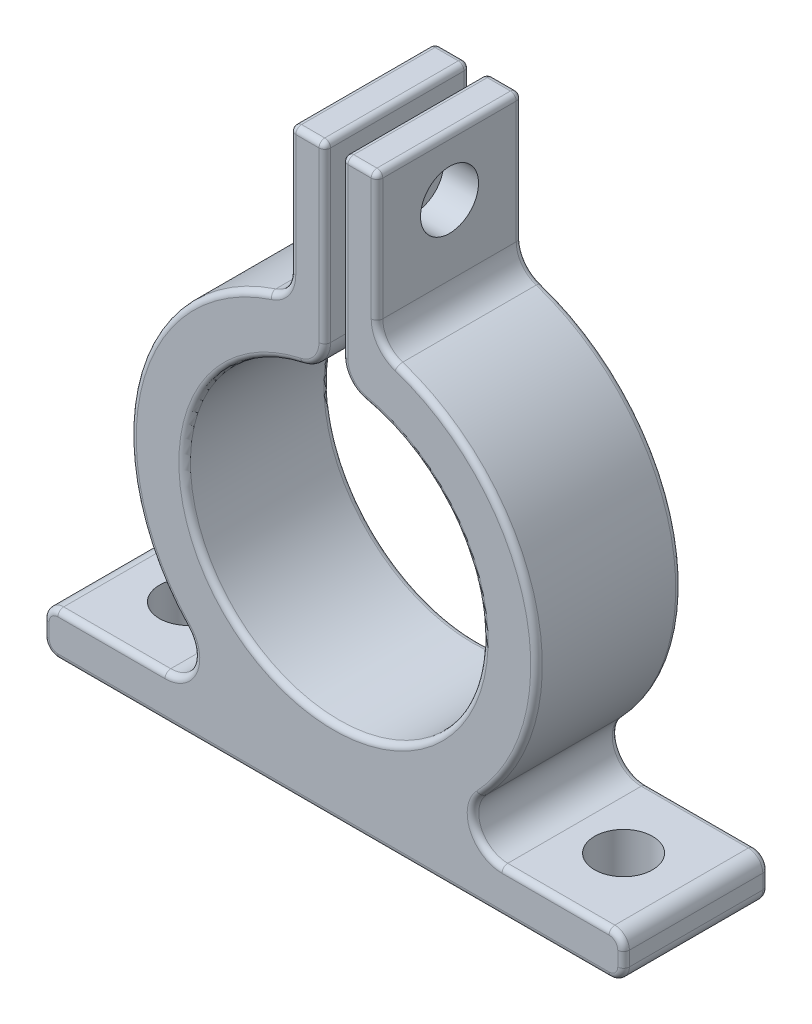
SolidWorks part; units mm, degrees
ref_plane "前视基准面" through (0, 0, 0) normal (0, 0, 1) x (1, 0, 0)
ref_plane "上视基准面" through (0, 0, 0) normal (0, 1, 0) x (1, 0, 0)
ref_plane "右视基准面" through (0, 0, 0) normal (1, 0, 0) x (0, 0, -1)
sketch "草图1" plane through (0, 0, 0) normal (0, 0, 1) x (1, 0, 0)
  line L0 (-9.5, -6.5) -> (-5.8095, -6.5)
  line L1 (0, -2.1091) -> (0, -11.8916) construction
  line L2 (-10, -7) -> (-10, -7.5)
  line L3 (-9.5, -8) -> (9.5, -8)
  line L4 (9.5, -6.5) -> (5.8095, -6.5)
  line L5 (-1.5, 11.8) -> (-1.5, 7.5993)
  line L6 (1.5, 11.8) -> (1.5, 7.5993)
  line L7 (-0.3, 11.8) -> (-0.3, 5.9914)
  line L8 (0, 0) -> (0, -2.1091) construction
  line L9 (0.3, 5.9914) -> (0.3, 11.8)
  line L10 (-1.3, 12) -> (-0.5, 12)
  line L11 (1.3, 12) -> (0.5, 12)
  line L12 (10, -7) -> (10, -7.5)
  arc A0 (-1.088, 5.0141) -> (1.088, 5.0141) centre (0, 0) ccw
  arc A1 (2.1875, 6.6494) -> (5.0833, -4.8125) centre (0, 0) cw
  arc A2 (5.0833, -4.8125) -> (5.8095, -6.5) centre (5.8095, -5.5) ccw
  arc A3 (-5.0833, -4.8125) -> (-5.8095, -6.5) centre (-5.8095, -5.5) cw
  arc A4 (10, -7) -> (9.5, -6.5) centre (9.5, -7) ccw
  arc A5 (9.5, -8) -> (10, -7.5) centre (9.5, -7.5) ccw
  arc A6 (-9.5, -8) -> (-10, -7.5) centre (-9.5, -7.5) cw
  arc A7 (-10, -7) -> (-9.5, -6.5) centre (-9.5, -7) cw
  arc A8 (-2.1875, 6.6494) -> (-5.0833, -4.8125) centre (0, 0) ccw
  arc A9 (1.5, 11.8) -> (1.3, 12) centre (1.3, 11.8) ccw
  arc A10 (0.5, 12) -> (0.3, 11.8) centre (0.5, 11.8) ccw
  arc A11 (-0.3, 11.8) -> (-0.5, 12) centre (-0.5, 11.8) ccw
  arc A12 (-1.3, 12) -> (-1.5, 11.8) centre (-1.3, 11.8) ccw
  arc A13 (0.3, 5.9914) -> (1.088, 5.0141) centre (1.3, 5.9914) ccw
  arc A14 (-0.3, 5.9914) -> (-1.088, 5.0141) centre (-1.3, 5.9914) cw
  arc A15 (2.1875, 6.6494) -> (1.5, 7.5993) centre (2.5, 7.5993) cw
  arc A16 (-1.5, 7.5993) -> (-2.1875, 6.6494) centre (-2.5, 7.5993) cw
  point P13 (2.5981, -6.5)
  point P36 (-0.3, 12)
  point P49 (0, -8)
  dimension "D1" = 6.5
  dimension "D9" = 0.2
  dimension "D10" = 1
  dimension "D5" = 1.5
  dimension "D6" = 1.5
  dimension "D7" = 0.3
  dimension "D8" = 0.3
extrude "凸台-拉伸1" add sketch "草图1" along normal blind 5
sketch "草图3" plane through (0, -6.5, 0) normal (0, 1, 0) x (1, 0, 0)
  circle A0 centre (-7.5, -2.5) radius 1
  circle A1 centre (7.5, -2.5) radius 1
extrude "切除-拉伸1" cut sketch "草图3" against normal up to next
sketch "草图4" plane through (-1.5, 0, 0) normal (-1, 0, 0) x (0, 0, 1)
  circle A0 centre (2.5, 10) radius 1
extrude "切除-拉伸2" cut sketch "草图4" against normal up to surface (3 mm away) up to face at (1.5, 9.6997, 2.5)
fillet "圆角2" radius 0.2 56 edges at (1.6899, 7.013, 0) (1.5, 9.6997, 0) (1.4414, 11.9414, 0) (0.9, 12, 0) (0.3586, 11.9414, 0) (0.3, 8.8957, 0) (0.5215, 5.3637, 0) (0, -5.1308, 0) (-0.5215, 5.3637, 0) (-0.3, 8.8957, 0) (-0.3586, 11.9414, 0) (-0.9, 12, 0) (-1.4414, 11.9414, 0) (-1.5, 9.6997, 0) (-1.6899, 7.013, 0) (-6.7868, 1.7146, 0) (-4.8909, -5.8953, 0) (-7.6547, -6.5, 0) (-9.8536, -6.6464, 0) (-10, -7.25, 0) (-9.8536, -7.8536, 0) (-9.8536, -7.8536, 5) (-10, -7.25, 5) (-9.8536, -6.6464, 5) (-7.6547, -6.5, 5) (-4.8909, -5.8953, 5) (-6.7868, 1.7146, 5) (-1.6899, 7.013, 5) (-1.5, 9.6997, 5) (-1.4414, 11.9414, 5) (-0.9, 12, 5) (-0.3586, 11.9414, 5) (-0.3, 8.8957, 5) (-0.5215, 5.3637, 5) (0, -5.1308, 5) (0.5215, 5.3637, 5) (0.3, 8.8957, 5) (0.3586, 11.9414, 5) (0.9, 12, 5) (1.4414, 11.9414, 5) (1.5, 9.6997, 5) (1.6899, 7.013, 5) (7.6547, -6.5, 5) (9.8536, -6.6464, 5) (10, -7.25, 5) (9.8536, -7.8536, 5) (0, -8, 5) (6.7868, 1.7146, 5) (4.8909, -5.8953, 5) (6.7868, 1.7146, 0) (0, -8, 0) (9.8536, -7.8536, 0) (10, -7.25, 0) (9.8536, -6.6464, 0) (7.6547, -6.5, 0) (4.8909, -5.8953, 0)
